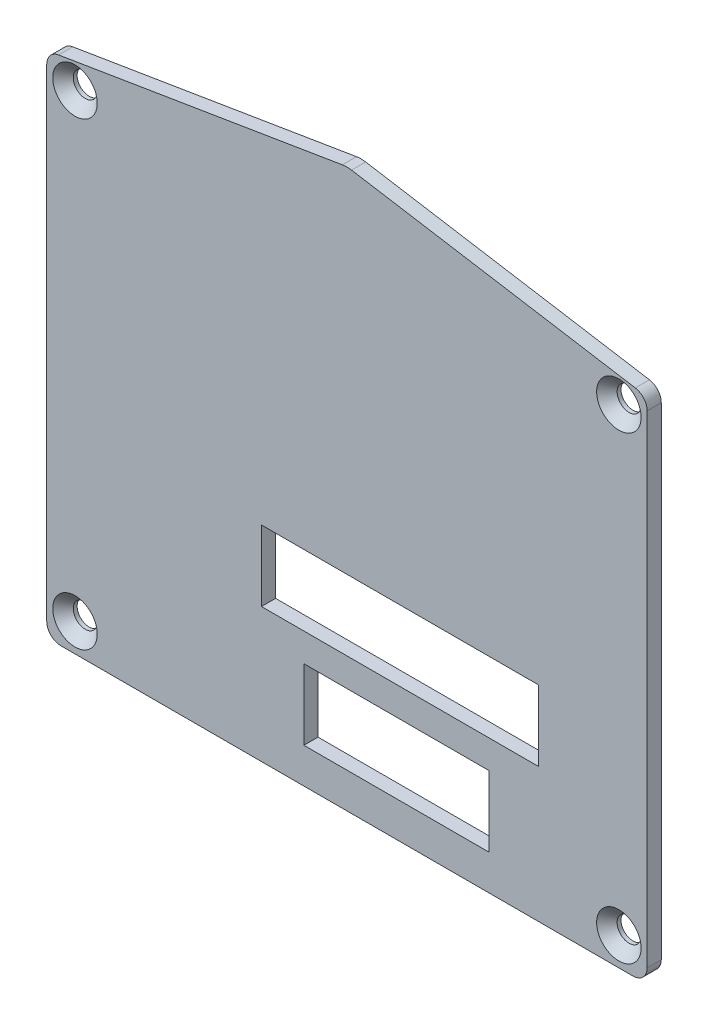
SolidWorks part; units mm, degrees
ref_plane "Piano frontale" through (0, 0, 0) normal (0, 0, 1) x (1, 0, 0)
ref_plane "Piano superiore" through (0, 0, 0) normal (0, 1, 0) x (1, 0, 0)
ref_plane "Piano destro" through (0, 0, 0) normal (1, 0, 0) x (0, 0, -1)
sketch "Schizzo1" plane through (0, 0, 0) normal (0, 0, 1) x (1, 0, 0)
  line L0 (-42.5, 36) -> (0, 43)
  line L1 (-42.5, -36) -> (42.5, -36)
  line L2 (-42.5, -36) -> (-42.5, 36)
  line L3 (-42.5, 36) -> (42.5, 36)
  line L4 (42.5, -36) -> (42.5, 36)
  line L5 (-42.5, -36) -> (42.5, 36) construction
  line L6 (-42.5, 36) -> (42.5, -36) construction
  line L7 (0, 43) -> (42.5, 36)
  point P0 (0, 0)
  point P6 (0, 36)
  dimension "D1" = 85
  dimension "D2" = 72
  dimension "D3" = 7
extrude "Estrusione-Estrusione1" add sketch "Schizzo1" along normal blind 2 contours L1 L4 L3 L2 | L7 L0 L3
fillet "Raccordo1" radius 4 1 edges at (0, 43, 1)
fillet "Raccordo3" radius 2 1 edges at (42.5, 36, 1)
fillet "Raccordo4" radius 2 1 edges at (42.5, -36, 1)
fillet "Raccordo5" radius 2 1 edges at (-42.5, -36, 1)
fillet "Raccordo6" radius 2 1 edges at (-42.5, 36, 1)
sketch "Schizzo2" plane through (0, 0, 2) normal (0, 0, 1) x (1, 0, 0)
  line L1 (-12.1, -16.99) -> (27.1, -16.99)
  line L2 (-12.1, -16.99) -> (-12.1, -6.99)
  line L3 (-12.1, -6.99) -> (27.1, -6.99)
  line L4 (27.1, -16.99) -> (27.1, -6.99)
  line L5 (-12.1, -16.99) -> (27.1, -6.99) construction
  line L6 (-12.1, -6.99) -> (27.1, -16.99) construction
  line L7 (-6.1, -31) -> (20.1, -31)
  line L8 (-6.1, -31) -> (-6.1, -21)
  line L9 (-6.1, -21) -> (20.1, -21)
  line L10 (20.1, -31) -> (20.1, -21)
  line L11 (-6.1, -31) -> (20.1, -21) construction
  line L12 (-6.1, -21) -> (20.1, -31) construction
  line L16 (-40.5, -36) -> (40.5, -36) construction
  line L18 (42.5, -34) -> (42.5, 34.3025) construction
  point P0 (7.5, -11.99)
  point P5 (7, -26)
  point P10 (20.1, -26)
  point P14 (27.1, -11.99)
  dimension "D1" = 10
  dimension "D2" = 10
  dimension "D3" = 10
  dimension "D4" = 39.2
  dimension "D5" = 26.2
  dimension "D6" = 24.01
  dimension "D7" = 15.4
  dimension "D8" = 22.4
extrude "Taglio-Estrusione1" cut sketch "Schizzo2" against normal up to next
hole_wizard "Foro svasato per Vite M3-1" positions "Schizzo3" profile "Schizzo4" countersink size "M3" standard "Ansi Metric" end condition up to next
sketch "Schizzo3" plane through (0, 0, 2) normal (0, 0, 1) x (1, 0, 0)
  line L0 (-42.5, -34) -> (-42.5, 34.3025) construction
  line L1 (42.5, -34) -> (42.5, 34.3025) construction
  line L2 (-40.5, -36) -> (40.5, -36) construction
  point P0 (-38.5, 33.0759)
  point P2 (-38.5, -32)
  point P4 (38.5, -32)
  point P6 (38.5, 33.0759)
  dimension "D1" = 4
  dimension "D2" = 3.2
  dimension "D3" = 3.2
  dimension "D4" = 4
  dimension "D5" = 4
  dimension "D6" = 4
  dimension "D7" = 4
  dimension "D8" = 4
sketch "Schizzo4" plane through (-38.5, 33.0759, 2) normal (1, 0, 0) x (0, -1, 0)
  line L0 (0, 0) -> (0, 2)
  line L1 (0, 2) -> (1.7, 2)
  line L2 (1.7, 2) -> (1.7, 1.45)
  line L3 (1.7, 1.45) -> (3.15, 0)
  line L5 (3.15, 0) -> (0, 0)
  line L6 (-1.7, 1.45) -> (-3.15, 0) construction
  line L11 (0, -6.35) -> (0, 107.95) construction
  dimension "Thru Hole Dia." = 3.4
  dimension "Thru Hole Depth" = 2
  dimension "Near C'Sink Dia." = 6.3
  dimension "Near C'Sink Angle" = 90
